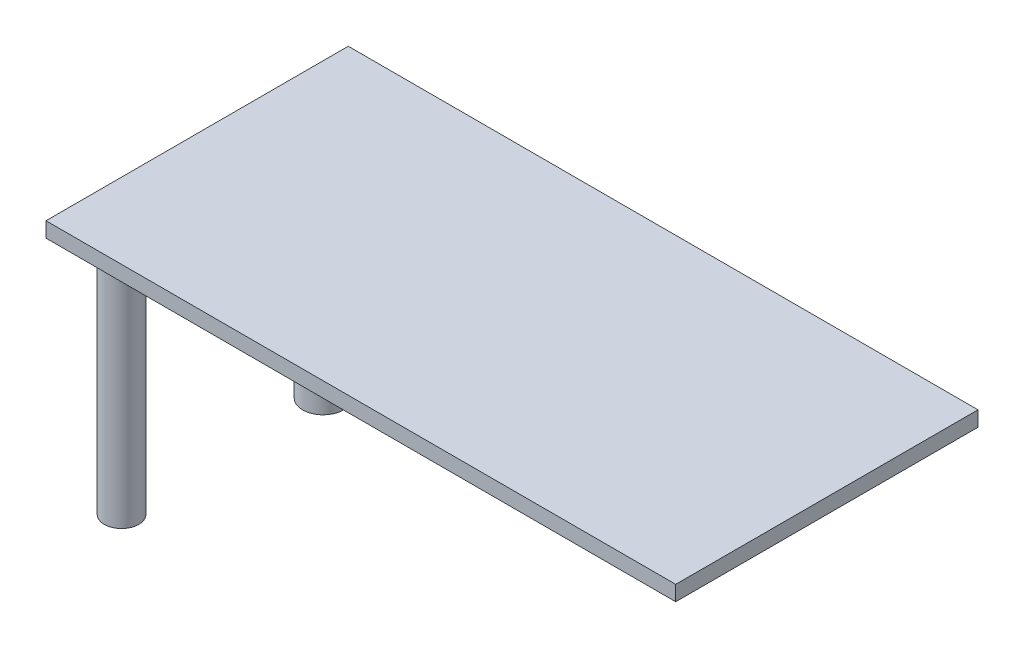
SolidWorks part; units mm, degrees
ref_plane "Front Plane" through (0, 0, 0) normal (0, 0, 1) x (1, 0, 0)
ref_plane "Top Plane" through (0, 0, 0) normal (0, 1, 0) x (1, 0, 0)
ref_plane "Right Plane" through (0, 0, 0) normal (1, 0, 0) x (0, 0, -1)
sketch "Sketch1" plane through (0, 0, 0) normal (0, 1, 0) x (1, 0, 0)
  line L1 (0, 0) -> (125, 0)
  line L2 (0, 0) -> (0, 60)
  line L3 (0, 60) -> (125, 60)
  line L4 (125, 0) -> (125, 60)
  dimension "D1" = 125
  dimension "D2" = 60
extrude "Boss-Extrude1" add sketch "Sketch1" along normal blind 3
sketch "Sketch2" plane through (0, 0, 0) normal (0, -1, 0) x (-1, 0, 0)
  circle A0 centre (-5, 10) radius 3.42
  circle A1 centre (-5, 50) radius 4.0544
  dimension "D1" = 5
  dimension "D2" = 5
  dimension "D3" = 10
  dimension "D4" = 50
extrude "Boss-Extrude2" add sketch "Sketch2" along normal blind 50
